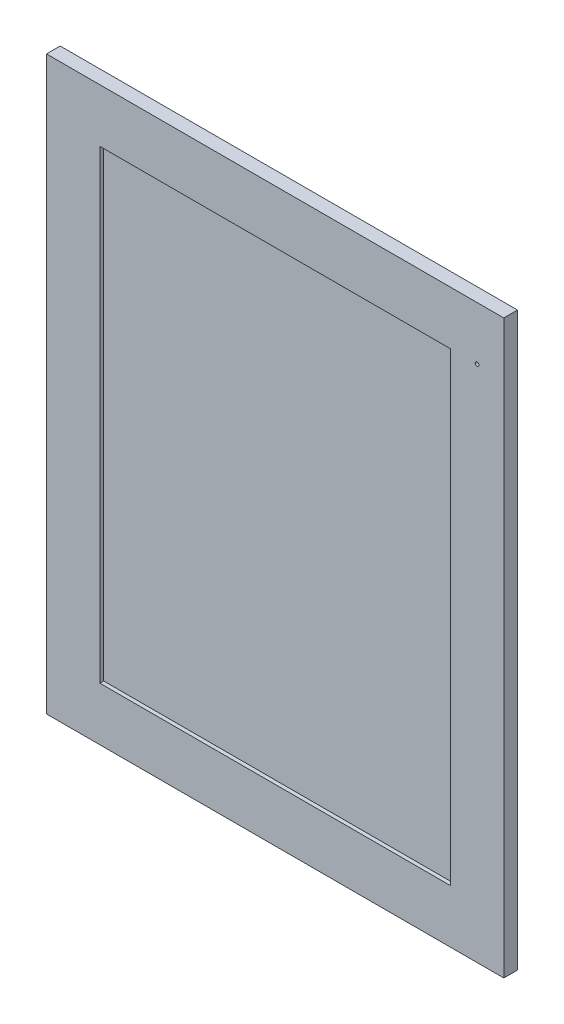
SolidWorks part; units mm, degrees
material "Faggio"
ref_plane "Front Plane" through (0, 0, 0) normal (0, 0, 1) x (1, 0, 0)
ref_plane "Top Plane" through (0, 0, 0) normal (0, 1, 0) x (1, 0, 0)
ref_plane "Right Plane" through (0, 0, 0) normal (1, 0, 0) x (0, 0, -1)
sketch "Schizzo1" plane through (0, 0, 0) normal (0, 0, 1) x (1, 0, 0)
  line L1 (0, -750) -> (-600, -750)
  line L2 (0, -750) -> (0, 0)
  line L3 (0, 0) -> (-600, 0)
  line L4 (-600, -750) -> (-600, 0)
  dimension "Altezza" = 750
  dimension "Larghezza" = 600
extrude "Pannello" add sketch "Schizzo1" against normal blind 18
sketch "Schizzo2" plane through (0, 0, 0) normal (0, 0, 1) x (1, 0, 0)
  line L1 (0, 0) -> (-600, 0) construction
  line L3 (0, -750) -> (0, 0) construction
  circle A0 centre (-35, -70) radius 2.5
  dimension "D3" = 5
  dimension "D1" = 70
  dimension "D2" = 35
extrude "ForoManiglia" cut sketch "Schizzo2" against normal through all
sketch "Schizzo3" plane through (0, 0, 0) normal (0, 0, 1) x (1, 0, 0)
  line L8 (-70, -680) -> (-70, -70)
  line L9 (-70, -70) -> (-530, -70)
  line L10 (-530, -70) -> (-530, -680)
  line L11 (-530, -680) -> (-70, -680)
  line L12 (-70, -680) -> (-70, -70)
  line L13 (-70, -70) -> (-530, -70)
  line L14 (-530, -70) -> (-530, -680)
  line L15 (-530, -680) -> (-70, -680)
  dimension "Telaio" = 70
extrude "Lavorazione" cut sketch "Schizzo3" against normal blind 5
